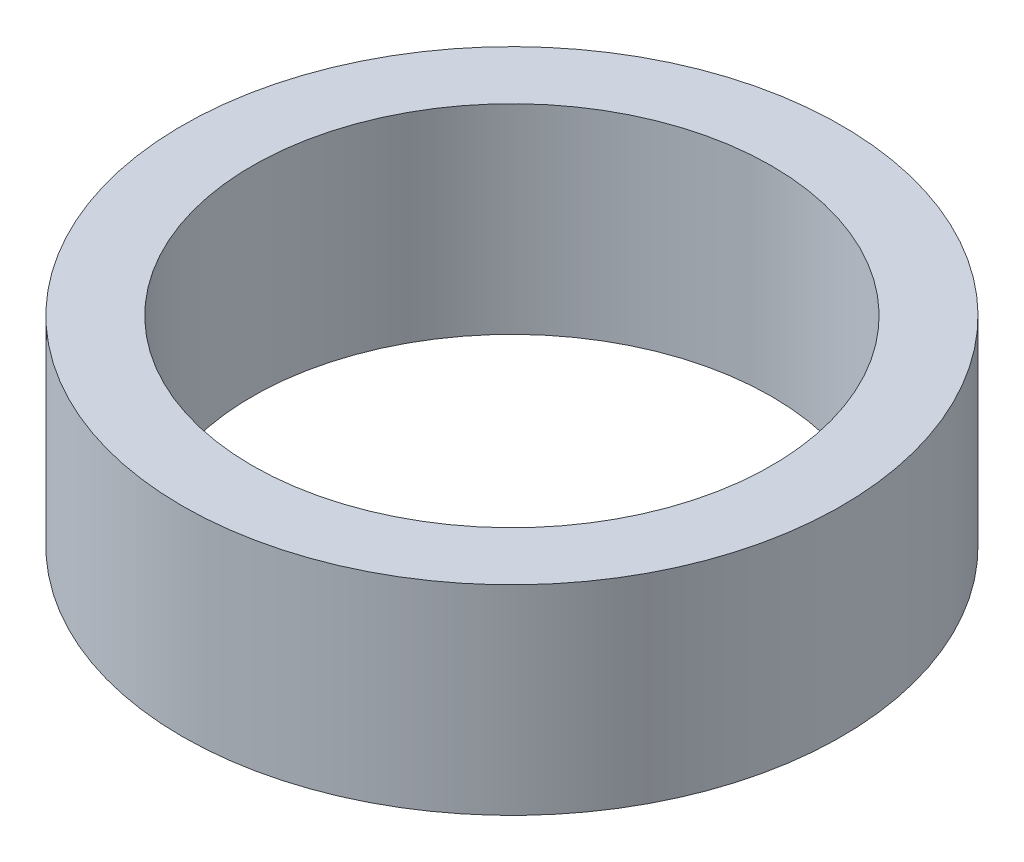
SolidWorks part; units mm, degrees
ref_plane "Front Plane" through (0, 0, 0) normal (0, 0, 1) x (1, 0, 0)
ref_plane "Top Plane" through (0, 0, 0) normal (0, 1, 0) x (1, 0, 0)
ref_plane "Right Plane" through (0, 0, 0) normal (1, 0, 0) x (0, 0, -1)
sketch "Sketch1" plane through (0, 0, 0) normal (0, 1, 0) x (1, 0, 0)
  circle A0 centre (0, 0) radius 16.5
  circle A1 centre (0, 0) radius 13
  dimension "D1" = 33
  dimension "D2" = 26
extrude "Boss-Extrude2" add sketch "Sketch1" along normal blind 10
